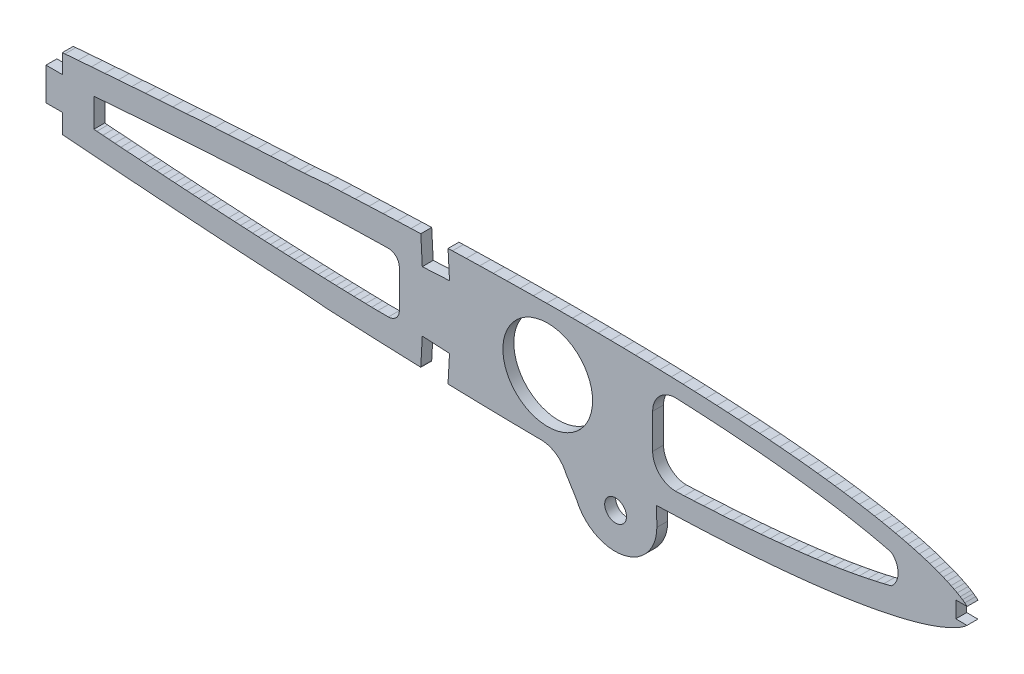
SolidWorks part; units mm, degrees
ref_plane "前视基准面" through (0, 0, 0) normal (0, 0, 1) x (1, 0, 0)
ref_plane "上视基准面" through (0, 0, 0) normal (0, 1, 0) x (1, 0, 0)
ref_plane "右视基准面" through (0, 0, 0) normal (1, 0, 0) x (0, 0, -1)
sketch "Model" plane through (0, 0, 0) normal (0, 0, 1) x (1, 0, 0)
  line L0 (172.8303, 26.4281) -> (170.783, 26.4481)
  line L1 (170.783, 26.4481) -> (170.783, 29.4481)
  line L2 (170.783, 29.4481) -> (172.8517, 29.4481)
  line L3 (72.6262, 17.4464) -> (72.8962, 22.4394)
  line L4 (72.8962, 22.4394) -> (77.8892, 22.1684)
  line L5 (77.8892, 22.1684) -> (77.6182, 17.1764)
  line L6 (72.6262, 38.5631) -> (72.8993, 33.4586)
  line L7 (72.8993, 33.4586) -> (77.8923, 33.7296)
  line L8 (77.8923, 33.7296) -> (77.6215, 38.719)
  line L9 (6.8633, 21.44) -> (7.34, 21.4019)
  line L10 (7.34, 21.4019) -> (9.774, 21.2099)
  line L11 (9.774, 21.2099) -> (12.207, 21.0189)
  line L12 (12.207, 21.0189) -> (14.642, 20.8309)
  line L13 (14.642, 20.8309) -> (17.126, 20.6429)
  line L14 (17.126, 20.6429) -> (19.609, 20.4569)
  line L15 (19.609, 20.4569) -> (22.094, 20.2759)
  line L16 (22.094, 20.2759) -> (24.62, 20.0939)
  line L17 (24.62, 20.0939) -> (27.144, 19.9169)
  line L18 (27.144, 19.9169) -> (29.67, 19.7419)
  line L19 (29.67, 19.7419) -> (32.225, 19.5679)
  line L20 (32.225, 19.5679) -> (34.78, 19.3979)
  line L21 (34.78, 19.3979) -> (37.335, 19.2329)
  line L22 (37.335, 19.2329) -> (39.912, 19.0719)
  line L23 (39.912, 19.0719) -> (42.488, 18.9159)
  line L24 (42.488, 18.9159) -> (45.065, 18.7629)
  line L25 (45.065, 18.7629) -> (47.65, 18.6119)
  line L26 (47.65, 18.6119) -> (50.235, 18.4639)
  line L27 (50.235, 18.4639) -> (51.2416, 18.4082)
  line L28 (51.2416, 18.4082) -> (55.403, 18.0551)
  line L29 (55.403, 18.0551) -> (57.989, 17.9301)
  line L30 (57.989, 17.9301) -> (60.566, 17.8121)
  line L31 (60.566, 17.8121) -> (63.142, 17.6991)
  line L32 (63.142, 17.6991) -> (65.719, 17.5921)
  line L33 (65.719, 17.5921) -> (68.274, 17.4911)
  line L34 (68.274, 17.4911) -> (70.828, 17.3961)
  line L35 (70.828, 17.3961) -> (72.6224, 17.3337)
  line L36 (77.6182, 17.1764) -> (78.434, 17.1521)
  line L37 (78.434, 17.1521) -> (80.96, 17.0851)
  line L38 (80.96, 17.0851) -> (83.444, 17.0251)
  line L39 (83.444, 17.0251) -> (85.928, 16.9721)
  line L40 (85.928, 16.9721) -> (88.412, 16.9271)
  line L41 (88.412, 16.9271) -> (90.847, 16.8901)
  line L42 (90.847, 16.8901) -> (93.28, 16.8611)
  line L43 (93.28, 16.8611) -> (94.7112, 16.8488)
  line L44 (115.8772, 17.0236) -> (116.434, 17.0381)
  line L45 (116.434, 17.0381) -> (118.574, 17.1041)
  line L46 (118.574, 17.1041) -> (120.713, 17.1791)
  line L47 (120.713, 17.1791) -> (122.853, 17.2651)
  line L48 (122.853, 17.2651) -> (124.898, 17.3581)
  line L49 (124.898, 17.3581) -> (126.942, 17.4601)
  line L50 (126.942, 17.4601) -> (128.986, 17.5741)
  line L51 (128.986, 17.5741) -> (130.928, 17.6941)
  line L52 (130.928, 17.6941) -> (132.868, 17.8241)
  line L53 (132.868, 17.8241) -> (134.808, 17.9671)
  line L54 (134.808, 17.9671) -> (136.638, 18.1131)
  line L55 (136.638, 18.1131) -> (138.467, 18.2711)
  line L56 (138.467, 18.2711) -> (140.296, 18.4421)
  line L57 (140.296, 18.4421) -> (142.009, 18.6131)
  line L58 (142.009, 18.6131) -> (143.72, 18.7961)
  line L59 (143.72, 18.7961) -> (145.431, 18.9931)
  line L60 (145.431, 18.9931) -> (147.018, 19.1881)
  line L61 (147.018, 19.1881) -> (148.604, 19.3971)
  line L62 (148.604, 19.3971) -> (150.187, 19.6201)
  line L63 (150.187, 19.6201) -> (151.644, 19.8391)
  line L64 (151.644, 19.8391) -> (153.097, 20.0721)
  line L65 (153.097, 20.0721) -> (154.549, 20.3201)
  line L66 (154.549, 20.3201) -> (155.869, 20.5591)
  line L67 (155.869, 20.5591) -> (157.186, 20.8131)
  line L68 (157.186, 20.8131) -> (158.5, 21.0831)
  line L69 (158.5, 21.0831) -> (159.678, 21.3411)
  line L70 (159.678, 21.3411) -> (160.853, 21.6151)
  line L71 (160.853, 21.6151) -> (162.024, 21.9061)
  line L72 (162.024, 21.9061) -> (163.056, 22.1781)
  line L73 (163.056, 22.1781) -> (164.084, 22.4661)
  line L74 (164.084, 22.4661) -> (165.107, 22.7731)
  line L75 (165.107, 22.7731) -> (165.991, 23.0571)
  line L76 (165.991, 23.0571) -> (166.867, 23.3591)
  line L77 (166.867, 23.3591) -> (167.736, 23.6831)
  line L78 (167.736, 23.6831) -> (168.465, 23.9751)
  line L79 (168.465, 23.9751) -> (169.187, 24.2841)
  line L80 (169.187, 24.2841) -> (169.901, 24.6121)
  line L81 (169.901, 24.6121) -> (170.476, 24.8931)
  line L82 (170.476, 24.8931) -> (171.041, 25.1921)
  line L83 (171.041, 25.1921) -> (171.594, 25.5161)
  line L84 (171.594, 25.5161) -> (172.015, 25.7921)
  line L85 (172.015, 25.7921) -> (172.422, 26.0881)
  line L86 (172.422, 26.0881) -> (172.809, 26.4081)
  line L87 (172.809, 26.4081) -> (172.8303, 26.4281)
  line L95 (78.434, 38.7441) -> (77.6215, 38.719)
  line L104 (51.2416, 37.4825) -> (50.235, 37.4269)
  line L105 (50.235, 37.4269) -> (47.65, 37.2789)
  line L106 (47.65, 37.2789) -> (45.065, 37.1279)
  line L107 (45.065, 37.1279) -> (42.488, 36.9749)
  line L108 (42.488, 36.9749) -> (39.912, 36.8189)
  line L109 (39.912, 36.8189) -> (37.335, 36.6579)
  line L110 (37.335, 36.6579) -> (34.78, 36.4929)
  line L111 (34.78, 36.4929) -> (32.225, 36.3229)
  line L112 (32.225, 36.3229) -> (29.67, 36.1489)
  line L113 (29.67, 36.1489) -> (27.144, 35.9739)
  line L114 (27.144, 35.9739) -> (24.62, 35.7969)
  line L115 (24.62, 35.7969) -> (22.094, 35.6149)
  line L116 (22.094, 35.6149) -> (19.609, 35.4339)
  line L117 (19.609, 35.4339) -> (17.126, 35.2479)
  line L118 (17.126, 35.2479) -> (14.642, 35.0599)
  line L119 (14.642, 35.0599) -> (12.207, 34.8719)
  line L120 (12.207, 34.8719) -> (9.774, 34.6809)
  line L121 (9.774, 34.6809) -> (7.34, 34.4889)
  line L122 (7.34, 34.4889) -> (6.8633, 34.4507)
  line L123 (158.9503, 31.0986) -> (157.5709, 31.4435)
  line L124 (157.5709, 31.4435) -> (156.1155, 31.7797)
  line L125 (156.1155, 31.7797) -> (154.6452, 32.097)
  line L126 (154.6452, 32.097) -> (153.1201, 32.402)
  line L127 (153.1201, 32.402) -> (151.5761, 32.6906)
  line L128 (151.5761, 32.6906) -> (149.9956, 32.9677)
  line L129 (149.9956, 32.9677) -> (148.4107, 33.2254)
  line L130 (148.4107, 33.2254) -> (146.7857, 33.4707)
  line L131 (146.7857, 33.4707) -> (145.1498, 33.7027)
  line L132 (145.1498, 33.7027) -> (143.4908, 33.9226)
  line L133 (143.4908, 33.9226) -> (141.8275, 34.128)
  line L134 (141.8275, 34.128) -> (140.1377, 34.3221)
  line L135 (140.1377, 34.3221) -> (138.4413, 34.5045)
  line L136 (138.4413, 34.5045) -> (136.7269, 34.6772)
  line L137 (136.7269, 34.6772) -> (135.0109, 34.8377)
  line L138 (135.0109, 34.8377) -> (133.2826, 34.9883)
  line L139 (133.2826, 34.9883) -> (131.5457, 35.1271)
  line L140 (131.5457, 35.1271) -> (129.7928, 35.2588)
  line L141 (129.7928, 35.2588) -> (128.0449, 35.3803)
  line L142 (128.0449, 35.3803) -> (126.2818, 35.4922)
  line L143 (126.2818, 35.4922) -> (124.5102, 35.597)
  line L144 (124.5102, 35.597) -> (122.7385, 35.6941)
  line L145 (122.7385, 35.6941) -> (120.959, 35.7814)
  line L146 (120.959, 35.7814) -> (119.3219, 35.857)
  line L147 (115.1623, 31.6236) -> (115.1623, 25.2422)
  line L148 (119.3219, 21.0089) -> (120.959, 21.0844)
  line L149 (120.959, 21.0844) -> (122.7385, 21.1718)
  line L150 (122.7385, 21.1718) -> (124.5102, 21.2688)
  line L151 (124.5102, 21.2688) -> (126.2818, 21.3736)
  line L152 (126.2818, 21.3736) -> (128.0449, 21.4855)
  line L153 (128.0449, 21.4855) -> (129.7928, 21.607)
  line L154 (129.7928, 21.607) -> (131.5457, 21.7388)
  line L155 (131.5457, 21.7388) -> (133.2826, 21.8775)
  line L156 (133.2826, 21.8775) -> (135.0109, 22.0282)
  line L157 (135.0109, 22.0282) -> (136.7269, 22.1886)
  line L158 (136.7269, 22.1886) -> (138.4413, 22.3613)
  line L159 (138.4413, 22.3613) -> (140.1377, 22.5438)
  line L160 (140.1377, 22.5438) -> (141.8275, 22.7378)
  line L161 (141.8275, 22.7378) -> (143.4908, 22.9433)
  line L162 (143.4908, 22.9433) -> (145.1498, 23.1632)
  line L163 (145.1498, 23.1632) -> (146.7857, 23.3951)
  line L164 (146.7857, 23.3951) -> (148.4107, 23.6405)
  line L165 (148.4107, 23.6405) -> (149.9956, 23.8982)
  line L166 (149.9956, 23.8982) -> (151.5761, 24.1752)
  line L167 (151.5761, 24.1752) -> (153.1201, 24.4639)
  line L168 (153.1201, 24.4639) -> (154.6452, 24.7689)
  line L169 (154.6452, 24.7689) -> (156.1155, 25.0861)
  line L170 (156.1155, 25.0861) -> (157.5709, 25.4223)
  line L171 (157.5709, 25.4223) -> (158.9503, 25.7672)
  line L172 (6.8633, 34.4507) -> (6.8633, 30.9672)
  line L174 (72.6262, 17.4464) -> (72.6224, 17.3337)
  line L175 (6.8633, 21.44) -> (6.8633, 24.9672)
  line L176 (6.8633, 24.9672) -> (3.8633, 24.9672)
  line L177 (3.8633, 24.9672) -> (3.8633, 30.9672)
  line L178 (3.8633, 30.9672) -> (6.8633, 30.9672)
  line L180 (51.2416, 37.4825) -> (55.403, 37.8411)
  line L181 (55.403, 37.8411) -> (57.989, 37.9661)
  line L182 (57.989, 37.9661) -> (60.566, 38.0841)
  line L183 (60.566, 38.0841) -> (63.142, 38.1971)
  line L184 (63.142, 38.1971) -> (65.719, 38.3041)
  line L185 (65.719, 38.3041) -> (68.274, 38.4051)
  line L186 (68.274, 38.4051) -> (70.828, 38.5001)
  line L187 (70.828, 38.5001) -> (72.6262, 38.5631)
  line L189 (78.434, 38.7441) -> (80.96, 38.8111)
  line L190 (80.96, 38.8111) -> (83.444, 38.8711)
  line L191 (83.444, 38.8711) -> (85.928, 38.9241)
  line L192 (85.928, 38.9241) -> (88.412, 38.9691)
  line L193 (88.412, 38.9691) -> (90.847, 39.0061)
  line L194 (90.847, 39.0061) -> (93.28, 39.0351)
  line L195 (93.28, 39.0351) -> (95.714, 39.0561)
  line L196 (95.714, 39.0561) -> (98.089, 39.0681)
  line L197 (98.089, 39.0681) -> (100.463, 39.0721)
  line L198 (100.463, 39.0721) -> (102.838, 39.0681)
  line L199 (102.838, 39.0681) -> (105.144, 39.0561)
  line L200 (105.144, 39.0561) -> (107.449, 39.0341)
  line L201 (107.449, 39.0341) -> (109.754, 39.0041)
  line L202 (109.754, 39.0041) -> (111.981, 38.9651)
  line L203 (111.981, 38.9651) -> (114.207, 38.9161)
  line L204 (114.207, 38.9161) -> (116.434, 38.8581)
  line L205 (116.434, 38.8581) -> (118.574, 38.7921)
  line L206 (118.574, 38.7921) -> (120.713, 38.7171)
  line L207 (120.713, 38.7171) -> (122.853, 38.6311)
  line L208 (122.853, 38.6311) -> (124.898, 38.5381)
  line L209 (124.898, 38.5381) -> (126.942, 38.4361)
  line L210 (126.942, 38.4361) -> (128.986, 38.3221)
  line L211 (128.986, 38.3221) -> (130.928, 38.2021)
  line L212 (130.928, 38.2021) -> (132.868, 38.0721)
  line L213 (132.868, 38.0721) -> (134.808, 37.9291)
  line L214 (134.808, 37.9291) -> (136.638, 37.7831)
  line L215 (136.638, 37.7831) -> (138.467, 37.6251)
  line L216 (138.467, 37.6251) -> (140.296, 37.4541)
  line L217 (140.296, 37.4541) -> (142.009, 37.2831)
  line L218 (142.009, 37.2831) -> (143.72, 37.1001)
  line L219 (143.72, 37.1001) -> (145.431, 36.9031)
  line L220 (145.431, 36.9031) -> (147.018, 36.7081)
  line L221 (147.018, 36.7081) -> (148.604, 36.4991)
  line L222 (148.604, 36.4991) -> (150.187, 36.2761)
  line L223 (150.187, 36.2761) -> (151.644, 36.0571)
  line L224 (151.644, 36.0571) -> (153.097, 35.8241)
  line L225 (153.097, 35.8241) -> (154.549, 35.5761)
  line L226 (154.549, 35.5761) -> (155.869, 35.3371)
  line L227 (155.869, 35.3371) -> (157.186, 35.0831)
  line L228 (157.186, 35.0831) -> (158.5, 34.8131)
  line L229 (158.5, 34.8131) -> (159.678, 34.5551)
  line L230 (159.678, 34.5551) -> (160.853, 34.2811)
  line L231 (160.853, 34.2811) -> (162.024, 33.9901)
  line L232 (162.024, 33.9901) -> (163.056, 33.7181)
  line L233 (163.056, 33.7181) -> (164.084, 33.4301)
  line L234 (164.084, 33.4301) -> (165.107, 33.1231)
  line L235 (165.107, 33.1231) -> (165.991, 32.8391)
  line L236 (165.991, 32.8391) -> (166.867, 32.5371)
  line L237 (166.867, 32.5371) -> (167.736, 32.2131)
  line L238 (167.736, 32.2131) -> (168.465, 31.9211)
  line L239 (168.465, 31.9211) -> (169.187, 31.6121)
  line L240 (169.187, 31.6121) -> (169.901, 31.2841)
  line L241 (169.901, 31.2841) -> (170.476, 31.0031)
  line L242 (170.476, 31.0031) -> (171.041, 30.7041)
  line L243 (171.041, 30.7041) -> (171.594, 30.3801)
  line L244 (171.594, 30.3801) -> (172.015, 30.1041)
  line L245 (172.015, 30.1041) -> (172.422, 29.8081)
  line L246 (172.422, 29.8081) -> (172.8517, 29.4481)
  line L248 (99.2351, 13.7945) -> (101.2257, 10.5693)
  line L249 (115.932, 13.5529) -> (115.8772, 17.0236)
  line L250 (12.645, 30.423) -> (13.1969, 30.4661)
  line L251 (13.1969, 30.4661) -> (14.2943, 30.5509)
  line L252 (14.2943, 30.5509) -> (15.3933, 30.6346)
  line L253 (15.3933, 30.6346) -> (16.4961, 30.7174)
  line L254 (16.4961, 30.7174) -> (17.597, 30.8013)
  line L255 (17.597, 30.8013) -> (18.6942, 30.8825)
  line L256 (18.6942, 30.8825) -> (19.7951, 30.9627)
  line L257 (19.7951, 30.9627) -> (20.8961, 31.043)
  line L258 (20.8961, 31.043) -> (21.9939, 31.1219)
  line L259 (21.9939, 31.1219) -> (23.0947, 31.1998)
  line L260 (23.0947, 31.1998) -> (24.1928, 31.2775)
  line L261 (24.1928, 31.2775) -> (25.2906, 31.3529)
  line L262 (25.2906, 31.3529) -> (26.3914, 31.4283)
  line L263 (26.3914, 31.4283) -> (27.4893, 31.5025)
  line L264 (27.4893, 31.5025) -> (28.5872, 31.5754)
  line L265 (28.5872, 31.5754) -> (29.6851, 31.6472)
  line L266 (29.6851, 31.6472) -> (30.7817, 31.7178)
  line L267 (30.7817, 31.7178) -> (31.8794, 31.7871)
  line L268 (31.8794, 31.7871) -> (32.9791, 31.8554)
  line L269 (32.9791, 31.8554) -> (34.0758, 31.9236)
  line L270 (34.0758, 31.9236) -> (35.1717, 31.9892)
  line L271 (35.1717, 31.9892) -> (36.2703, 32.0539)
  line L272 (36.2703, 32.0539) -> (37.3669, 32.1185)
  line L273 (37.3669, 32.1185) -> (38.4616, 32.1806)
  line L274 (38.4616, 32.1806) -> (39.5582, 32.2416)
  line L275 (39.5582, 32.2416) -> (40.6548, 32.3014)
  line L276 (40.6548, 32.3014) -> (41.7495, 32.3599)
  line L277 (41.7495, 32.3599) -> (42.8461, 32.4161)
  line L278 (42.8461, 32.4161) -> (43.9416, 32.4723)
  line L279 (43.9416, 32.4723) -> (45.0362, 32.526)
  line L280 (45.0362, 32.526) -> (46.1329, 32.5786)
  line L281 (46.1329, 32.5786) -> (47.2284, 32.63)
  line L282 (47.2284, 32.63) -> (48.3218, 32.6802)
  line L283 (48.3218, 32.6802) -> (49.4183, 32.728)
  line L284 (49.4183, 32.728) -> (50.512, 32.7758)
  line L285 (50.512, 32.7758) -> (51.6054, 32.8199)
  line L286 (51.6054, 32.8199) -> (52.7009, 32.8642)
  line L287 (52.7009, 32.8642) -> (53.7932, 32.906)
  line L288 (53.7932, 32.906) -> (54.8867, 32.9465)
  line L289 (54.8867, 32.9465) -> (55.979, 32.9847)
  line L290 (55.979, 32.9847) -> (57.0713, 33.0218)
  line L291 (57.0713, 33.0218) -> (58.1635, 33.0564)
  line L292 (58.1635, 33.0564) -> (59.2577, 33.0899)
  line L293 (59.2577, 33.0899) -> (60.3481, 33.122)
  line L294 (60.3481, 33.122) -> (61.4373, 33.1506)
  line L295 (61.4373, 33.1506) -> (62.5304, 33.1781)
  line L296 (62.5304, 33.1781) -> (63.6202, 33.2044)
  line L297 (63.6202, 33.2044) -> (64.7094, 33.2282)
  line L298 (64.7094, 33.2282) -> (65.7973, 33.2497)
  line L299 (65.7973, 33.2497) -> (66.6486, 33.2646)
  line L300 (68.6837, 31.2649) -> (68.6837, 24.3659)
  line L301 (66.6837, 22.3659) -> (64.7087, 22.3659)
  line L302 (64.7087, 22.3659) -> (63.6202, 22.3898)
  line L303 (63.6202, 22.3898) -> (62.5304, 22.416)
  line L304 (62.5304, 22.416) -> (61.4373, 22.4435)
  line L305 (61.4373, 22.4435) -> (60.3481, 22.4721)
  line L306 (60.3481, 22.4721) -> (59.2577, 22.5043)
  line L307 (59.2577, 22.5043) -> (58.1635, 22.5378)
  line L308 (58.1635, 22.5378) -> (57.0713, 22.5724)
  line L309 (57.0713, 22.5724) -> (55.979, 22.6094)
  line L310 (55.979, 22.6094) -> (54.8867, 22.6476)
  line L311 (54.8867, 22.6476) -> (53.7932, 22.6882)
  line L312 (53.7932, 22.6882) -> (52.7009, 22.73)
  line L313 (52.7009, 22.73) -> (51.6054, 22.7742)
  line L314 (51.6054, 22.7742) -> (50.512, 22.8184)
  line L315 (50.512, 22.8184) -> (49.4183, 22.8661)
  line L316 (49.4183, 22.8661) -> (48.3218, 22.914)
  line L317 (48.3218, 22.914) -> (47.2284, 22.9641)
  line L318 (47.2284, 22.9641) -> (46.1329, 23.0155)
  line L319 (46.1329, 23.0155) -> (45.0362, 23.0682)
  line L320 (45.0362, 23.0682) -> (43.9416, 23.1219)
  line L321 (43.9416, 23.1219) -> (42.8461, 23.1781)
  line L322 (42.8461, 23.1781) -> (41.7495, 23.2343)
  line L323 (41.7495, 23.2343) -> (40.6548, 23.2928)
  line L324 (40.6548, 23.2928) -> (39.5582, 23.3526)
  line L325 (39.5582, 23.3526) -> (38.4616, 23.4136)
  line L326 (38.4616, 23.4136) -> (37.3669, 23.4756)
  line L327 (37.3669, 23.4756) -> (36.2703, 23.5402)
  line L328 (36.2703, 23.5402) -> (35.1717, 23.6049)
  line L329 (35.1717, 23.6049) -> (34.0758, 23.6706)
  line L330 (34.0758, 23.6706) -> (32.9791, 23.7387)
  line L331 (32.9791, 23.7387) -> (31.8794, 23.807)
  line L332 (31.8794, 23.807) -> (30.7817, 23.8764)
  line L333 (30.7817, 23.8764) -> (29.6851, 23.9469)
  line L334 (29.6851, 23.9469) -> (28.5872, 24.0187)
  line L335 (28.5872, 24.0187) -> (27.4893, 24.0916)
  line L336 (27.4893, 24.0916) -> (26.3914, 24.1658)
  line L337 (26.3914, 24.1658) -> (25.2906, 24.2413)
  line L338 (25.2906, 24.2413) -> (24.1928, 24.3166)
  line L339 (24.1928, 24.3166) -> (23.0947, 24.3944)
  line L340 (23.0947, 24.3944) -> (21.9939, 24.4722)
  line L341 (21.9939, 24.4722) -> (20.8961, 24.5511)
  line L342 (20.8961, 24.5511) -> (19.7951, 24.6314)
  line L343 (19.7951, 24.6314) -> (18.6942, 24.7117)
  line L344 (18.6942, 24.7117) -> (17.597, 24.7929)
  line L345 (17.597, 24.7929) -> (16.4961, 24.8767)
  line L346 (16.4961, 24.8767) -> (15.3933, 24.9595)
  line L347 (15.3933, 24.9595) -> (14.2943, 25.0432)
  line L348 (14.2943, 25.0432) -> (13.1969, 25.128)
  line L349 (13.1969, 25.128) -> (12.6454, 25.1712)
  line L350 (12.645, 30.423) -> (12.6454, 25.1712)
  arc A0 (158.9503, 25.7672) -> (158.9503, 31.0986) centre (156.7173, 28.4329) ccw
  circle A1 centre (95.9154, 27.7699) radius 8.2247
  arc A2 (101.2257, 10.5693) -> (115.932, 13.5529) centre (108.2728, 13.5699) ccw
  circle A3 centre (108.3617, 12.4614) radius 2
  arc A4 (119.3219, 35.857) -> (115.1623, 31.6236) centre (119.3963, 31.6236) ccw
  arc A5 (115.1623, 25.2422) -> (119.3219, 21.0089) centre (119.3963, 25.2422) ccw
  arc A6 (99.2351, 13.7945) -> (94.7112, 16.8488) centre (94.629, 11.8495) ccw
  arc A7 (68.6837, 31.2649) -> (66.6486, 33.2646) centre (66.6837, 31.2649) ccw
  arc A8 (66.6837, 22.3659) -> (68.6837, 24.3659) centre (66.6837, 24.3659) ccw
  point P28 (0, 0)
  point P33 (12.6254, 30.423)
  point P36 (0, 0)
  point P72 (172.8831, 29.5538)
  point P117 (77.8923, 38.8346)
  point P118 (90.847, 39.1132)
  point P119 (78.434, 38.7617)
  point P120 (72.6245, 38.5822)
  point P121 (72.6262, 38.5631)
  point P122 (85.928, 39.0351)
  point P123 (83.444, 38.9691)
  point P124 (80.96, 38.9231)
  point P126 (0, 0)
  point P201 (72.6441, 38.5617)
  point P202 (94.6687, 16.7631)
  point P203 (94.7112, 16.8343)
  point P204 (0, 0)
  point P217 (93.2559, 39.1647)
  point P276 (77.5517, 38.719)
  point P377 (93.313, 39.1649)
  point P378 (172.8517, 29.4881)
  point P379 (0, 0)
  point P380 (0, 0)
  point P381 (6.8438, 34.4507)
  point P382 (70.828, 38.5895)
extrude "凸台-拉伸1" add sketch "Model" along normal blind 2
